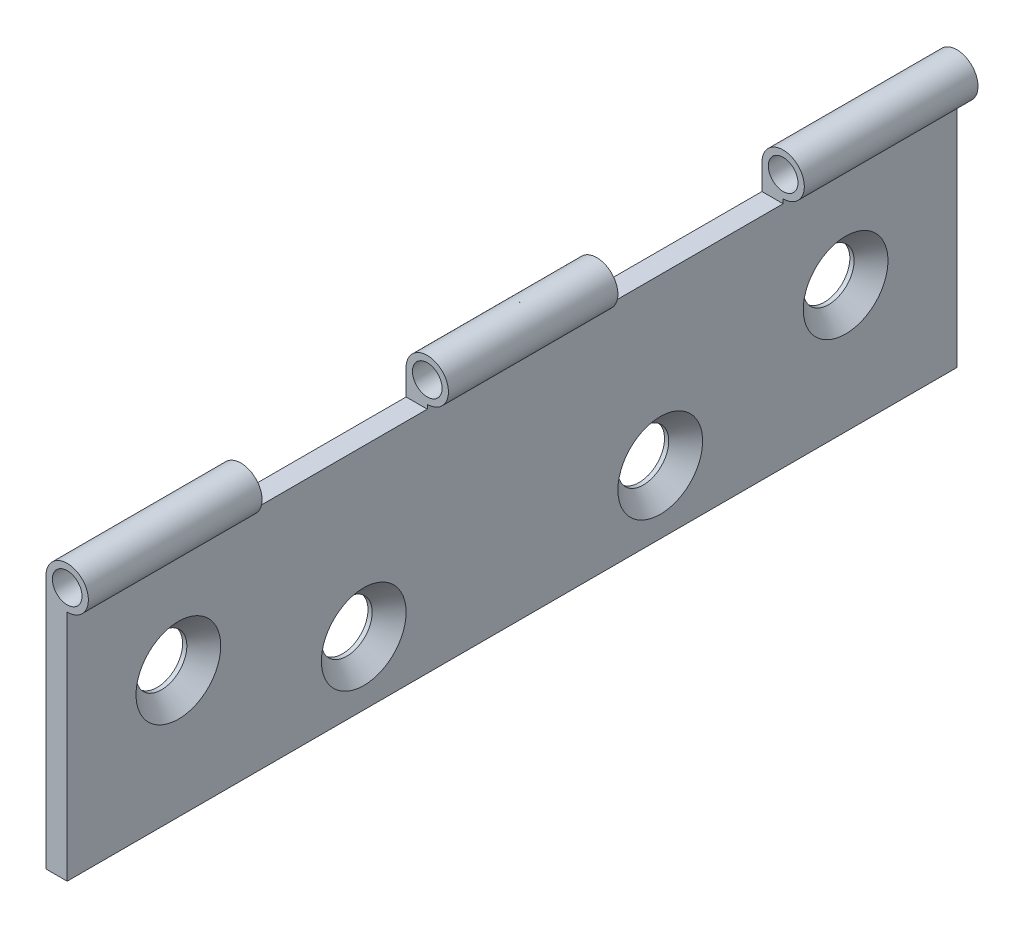
SolidWorks part; units mm, degrees
ref_plane "Спереди" through (0, 0, 0) normal (0, 0, 1) x (1, 0, 0)
ref_plane "Сверху" through (0, 0, 0) normal (0, 1, 0) x (1, 0, 0)
ref_plane "Справа" through (0, 0, 0) normal (1, 0, 0) x (0, 0, -1)
sketch "Эскиз1" plane through (0, 0, 0) normal (0, 0, 1) x (1, 0, 0)
  line L0 (0, 0) -> (0, 60)
  dimension "D1" = 60
extrude "Вытянуть-Тонкостенный2" add sketch "Эскиз1" along normal mid plane 210 thin contours L0
sketch "Эскиз2" plane through (0, 0, 105) normal (0, 0, 1) x (1, 0, 0)
  circle A0 centre (5, 60) radius 5
sweep "По траектории1" add profiles "Эскиз2" path edge at (0, 60, 0)
sketch "Эскиз3" plane through (0, 0, 105) normal (0, 0, 1) x (1, 0, 0)
  circle A0 centre (5, 60) radius 3.5
  dimension "D1" = 7
extrude "Вырез-Вытянуть1" cut sketch "Эскиз3" against normal through all
hole_wizard "Зенковка для  винта с плоской головкой M101" positions "Эскиз7" profile "Эскиз8" countersink size "M10" standard "Ansi Metric" end condition through all
sketch "Эскиз7" plane through (5, 0, 0) normal (1, 0, 0) x (0, 0, -1)
  line L0 (-105, 0) -> (-105, 55) construction
  line L1 (-105, 0) -> (105, 0) construction
  point P0 (-78.75, 30)
  point P2 (-35, 15)
  dimension "D1" = 26.25
  dimension "D2" = 30
  dimension "D3" = 70
  dimension "D4" = 15
sketch "Эскиз8" plane through (5, 30, 78.75) normal (0, 1, 0) x (0, 0, -1)
  line L0 (0, 0) -> (0, 5)
  line L1 (0, 5) -> (6, 5)
  line L2 (6, 5) -> (6, 4)
  line L3 (6, 4) -> (10, 0)
  line L5 (10, 0) -> (0, 0)
  line L6 (-6, 4) -> (-10, 0) construction
  line L11 (0, -6.35) -> (0, 107.95) construction
  dimension "Диаметр сквозного отверстия" = 12
  dimension "Глубина сквозного отверстия" = 5
  dimension "Диаметр передней зенковки" = 20
  dimension "Угол передней зенковки" = 90
mirror "Зеркальное отражение1" about plane through (0, 0, 0) normal (0, 0, 1) of "Зенковка для  винта с плоской головкой M101"
sketch "Эскиз10" plane through (5, 0, 0) normal (1, 0, 0) x (0, 0, -1)
  line L0 (-63, 54) -> (-63, 65)
  line L1 (105, 60) -> (105, 65) construction
  line L2 (-105, 54) -> (105, 54)
  line L3 (-105, 54) -> (105, 54)
  line L4 (105, 55) -> (105, 60) construction
  line L5 (-105, 65) -> (-105, 60) construction
  line L6 (-105, 60) -> (-105, 55) construction
  line L7 (105, 60) -> (105, 65)
  line L8 (105, 54) -> (105, 60)
  line L9 (-105, 65) -> (-105, 60)
  line L10 (-105, 60) -> (-105, 54)
  line L11 (-105, 65) -> (105, 65)
  line L12 (-21, 54) -> (-21, 65)
  line L13 (0, 0) -> (0, 65) construction
  line L14 (21, 54) -> (21, 65)
  line L15 (63, 54) -> (63, 65)
  dimension "D2" = 42
  dimension "D3" = 42
  dimension "D1" = 1
sketch "Эскиз12" plane through (5, 0, 0) normal (1, 0, 0) x (0, 0, -1)
  line L0 (-105, 54) -> (105, 54) construction
  line L3 (-105, 65) -> (105, 65) construction
  line L6 (-64, 54) -> (-20, 54)
  line L9 (-64, 65) -> (-20, 65)
  line L12 (20, 54) -> (64, 54)
  line L13 (20, 65) -> (64, 65)
  line L14 (64, 54) -> (64, 65)
  line L15 (64, 54) -> (64, 65)
  line L16 (0, 54) -> (0, 65) construction
  line L17 (20, 54) -> (20, 65)
  line L18 (20, 54) -> (20, 65)
  line L19 (-64, 54) -> (-64, 65)
  line L20 (-20, 54) -> (-20, 65)
  dimension "D1" = 1
  dimension "D2" = 1
extrude "vir_2" cut sketch "Эскиз12" against normal through all and the other way through all
sketch "Эскиз_vir3" plane through (5, 0, 0) normal (1, 0, 0) x (0, 0, -1)
  line L0 (-105, 54) -> (105, 54) construction
  line L1 (105, 54) -> (105, 60) construction
  line L2 (105, 60) -> (105, 65) construction
  line L3 (-105, 65) -> (105, 65) construction
  line L4 (-105, 65) -> (-105, 60) construction
  line L5 (-105, 60) -> (-105, 54) construction
  line L6 (-105, 54) -> (-62, 54)
  line L7 (105, 54) -> (105, 60)
  line L8 (105, 60) -> (105, 65)
  line L9 (-105, 65) -> (-62, 65)
  line L10 (-105, 65) -> (-105, 60)
  line L11 (-105, 60) -> (-105, 54)
  line L14 (-62, 54) -> (-62, 65)
  line L15 (-62, 54) -> (-62, 65)
  line L16 (0, 54) -> (0, 65) construction
  line L17 (-22, 54) -> (-22, 65)
  line L18 (-22, 54) -> (-22, 65)
  line L19 (22, 54) -> (22, 65)
  line L20 (62, 54) -> (62, 65)
  line L21 (-22, 65) -> (22, 65)
  line L22 (-22, 54) -> (22, 54)
  line L23 (62, 65) -> (105, 65)
  line L24 (62, 54) -> (105, 54)
  dimension "D1" = 1
  dimension "D2" = 1
extrude "vir_3" [suppressed] cut sketch "Эскиз_vir3" against normal through all and the other way through all
equation "\"depth\"= 5"
equation "\"width\"= 60"
equation "\"length\" = 210"
equation "\"D1@Вытянуть-Тонкостенный2\"= \"length\""
equation "\"D1@Эскиз1\"= \"width\""
equation "\"D5@Вытянуть-Тонкостенный2\"= \"depth\""
equation "\"D1@Эскиз3\"= \"depth\" / 5 * 7"
equation "\"D1@Эскиз7\"= \"length\" / 8"
equation "\"D2@Эскиз7\"= \"width\" / 2"
equation "\"D3@Эскиз7\"= \"length\" / 3"
equation "\"D4@Эскиз7\"= \"width\" / 4"
equation "\"D2@Эскиз10\"= \"length\" / 5"
equation "\"D3@Эскиз10\"= \"length\" / 5"
equation "\"D4@Эскиз4\"= \"length\" / 3"
equation "\"D3@Эскиз4\"= \"width\" / 2"
equation "\"D2@Эскиз4\"= \"width\" / 4"
equation "\"D1@Эскиз4\"= \"width\" / 4"
